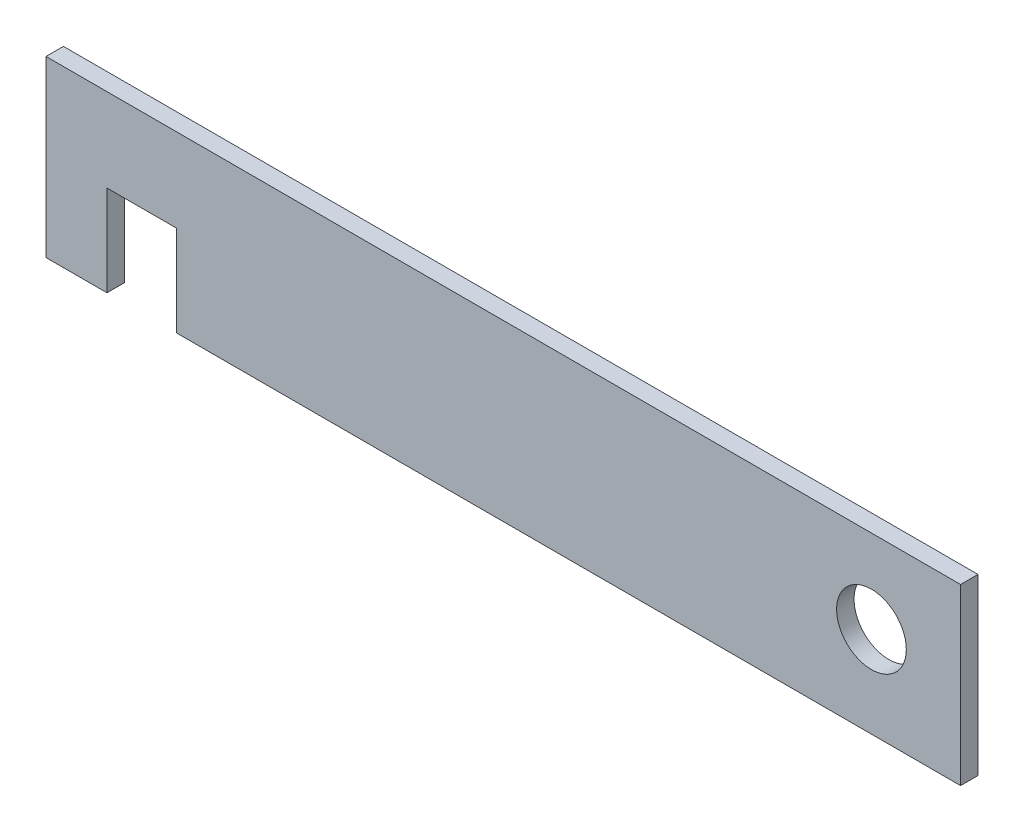
SolidWorks part; units mm, degrees
ref_plane "Front Plane" through (0, 0, 0) normal (0, 0, 1) x (1, 0, 0)
ref_plane "Top Plane" through (0, 0, 0) normal (0, 1, 0) x (1, 0, 0)
ref_plane "Right Plane" through (0, 0, 0) normal (1, 0, 0) x (0, 0, -1)
sketch "Sketch1" plane through (0, 0, 0) normal (0, 0, 1) x (1, 0, 0)
  line L0 (-227.5, 0) -> (-227.5, 52.0874)
  line L1 (-262.5, 100) -> (262.5, 100)
  line L2 (-262.5, 100) -> (-262.5, 0)
  line L3 (-262.5, 0) -> (-227.5, 0)
  line L4 (262.5, 100) -> (262.5, 0)
  line L5 (-227.5, 52.0874) -> (-187.5, 52.0874)
  line L6 (-187.5, 52.0874) -> (-187.5, 0)
  line L7 (-187.5, 0) -> (262.5, 0)
  circle A0 centre (211.3387, 52.0874) radius 20
  dimension "D6" = 40
  dimension "D1" = 525
  dimension "D2" = 262.5
  dimension "D3" = 100
  dimension "D4" = 35
  dimension "D5" = 40
extrude "Boss-Extrude1" add sketch "Sketch1" along normal blind 10
